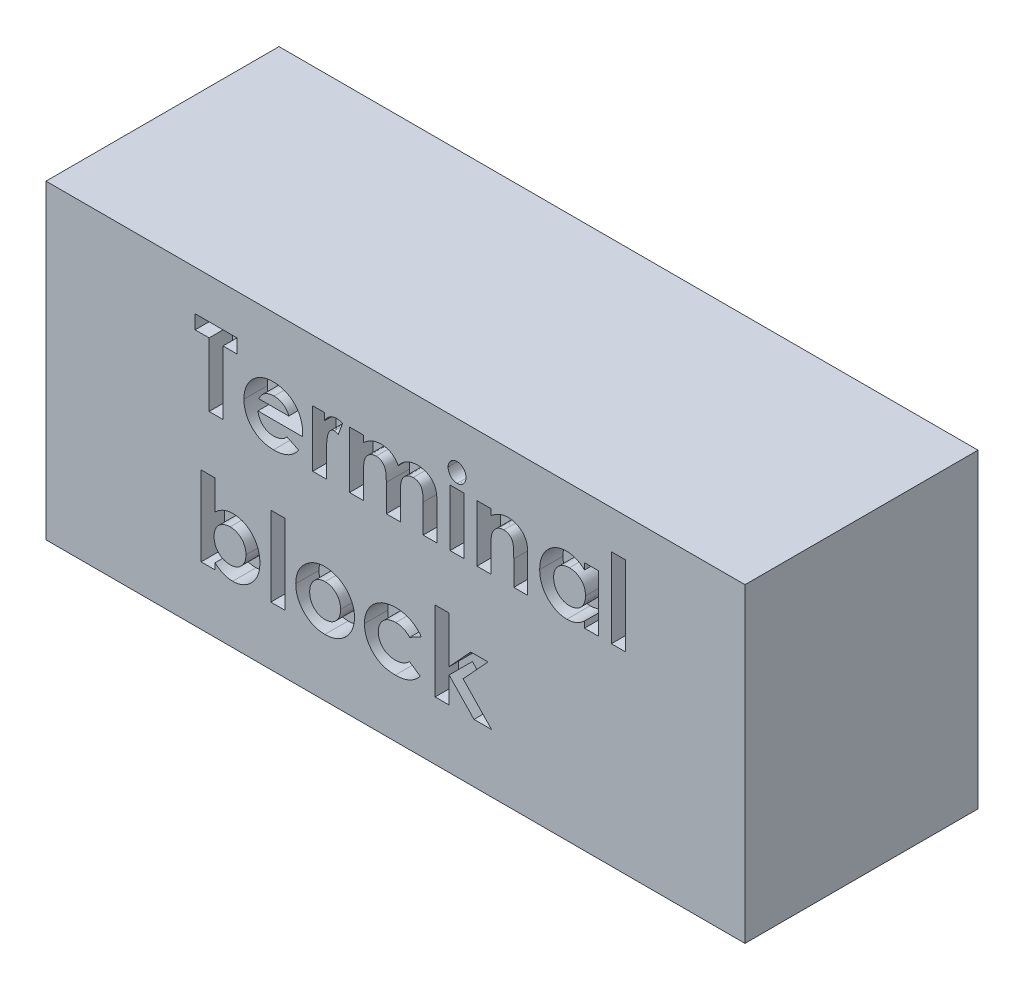
SolidWorks part; units mm, degrees
ref_plane "正面" through (0, 0, 0) normal (0, 0, 1) x (1, 0, 0)
ref_plane "平面" through (0, 0, 0) normal (0, 1, 0) x (1, 0, 0)
ref_plane "右側面" through (0, 0, 0) normal (1, 0, 0) x (0, 0, -1)
sketch "ｽｹｯﾁ1" plane through (0, 0, 0) normal (0, 0, 1) x (1, 0, 0)
  line L1 (0, 0) -> (90, 0)
  line L2 (0, 0) -> (0, 40)
  line L3 (0, 40) -> (90, 40)
  line L4 (90, 0) -> (90, 40)
  dimension "D1" = 40
  dimension "D2" = 90
extrude "ﾎﾞｽ - 押し出し1" add sketch "ｽｹｯﾁ1" along normal blind 30
sketch "ｽｹｯﾁ2" plane through (0, 0, 30) normal (0, 0, 1) x (1, 0, 0)
  text T0 "<b>Terminal </b>\r\n<b>block</b>" font "Century Gothic" height 10
extrude "ｶｯﾄ - 押し出し1" cut sketch "ｽｹｯﾁ2" against normal blind 3
